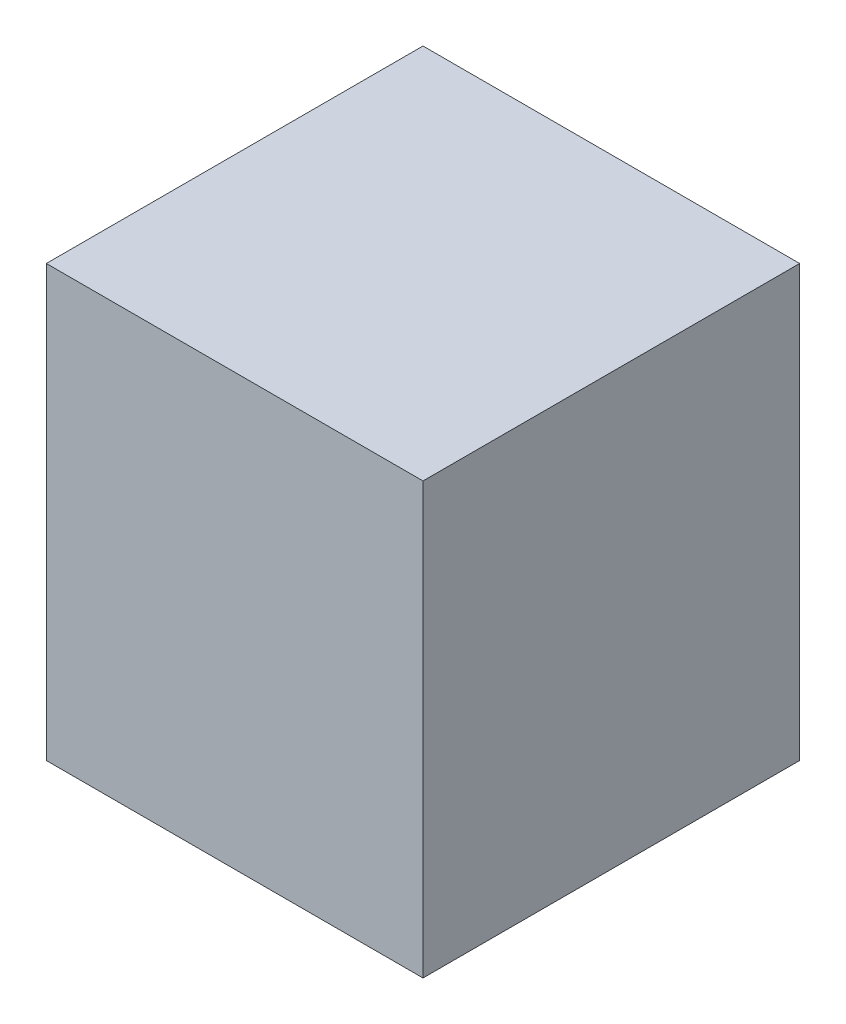
SolidWorks part; units mm, degrees
ref_plane "Front Plane" through (0, 0, 0) normal (0, 0, 1) x (1, 0, 0)
ref_plane "Top Plane" through (0, 0, 0) normal (0, 1, 0) x (1, 0, 0)
ref_plane "Right Plane" through (0, 0, 0) normal (1, 0, 0) x (0, 0, -1)
sketch "Sketch1" plane through (0, 0, 0) normal (0, 0, 1) x (1, 0, 0)
  line L1 (-60, 70) -> (60, 70)
  line L2 (-60, 70) -> (-60, -70)
  line L3 (-60, -70) -> (60, -70)
  line L4 (60, 70) -> (60, -70)
  line L5 (-60, 70) -> (60, -70) construction
  line L6 (-60, -70) -> (60, 70) construction
  point P0 (0, 0)
  dimension "D1" = 120
  dimension "D2" = 140
extrude "Extrude-Thin1" add sketch "Sketch1" along normal mid plane 120 thin thin type one direction wall 10
sketch "Sketch2" plane through (0, 0, 60) normal (0, 0, 1) x (1, 0, 0)
  line L1 (-70, 80) -> (70, 80)
  line L2 (-70, 80) -> (-70, -80)
  line L3 (-70, -80) -> (70, -80)
  line L4 (70, 80) -> (70, -80)
  line L5 (-70, 80) -> (70, -80) construction
  line L6 (-70, -80) -> (70, 80) construction
  point P0 (0, 0)
extrude "Boss-Extrude1" add sketch "Sketch2" along normal blind 10
sketch "Sketch5" plane through (0, 0, -60) normal (0, 0, -1) x (-1, 0, 0)
  line L1 (-70, 80) -> (70, 80)
  line L2 (-70, 80) -> (-70, -80)
  line L3 (-70, -80) -> (70, -80)
  line L4 (70, 80) -> (70, -80)
  line L5 (-70, 80) -> (70, -80) construction
  line L6 (-70, -80) -> (70, 80) construction
  point P0 (0, 0)
extrude "Boss-Extrude2" add sketch "Sketch5" along normal blind 10
sketch "Sketch7" plane through (0, -80, 0) normal (0, -1, 0) x (1, 0, 0)
  line L1 (-60.7744, 62.5474) -> (60.7744, 62.5474)
  line L2 (-60.7744, 62.5474) -> (-60.7744, -62.5474)
  line L3 (-60.7744, -62.5474) -> (60.7744, -62.5474)
  line L4 (60.7744, 62.5474) -> (60.7744, -62.5474)
  line L5 (-60.7744, 62.5474) -> (60.7744, -62.5474) construction
  line L6 (-60.7744, -62.5474) -> (60.7744, 62.5474) construction
  point P0 (0, 0)
extrude "Cut-Extrude2" cut sketch "Sketch7" against normal blind 40
